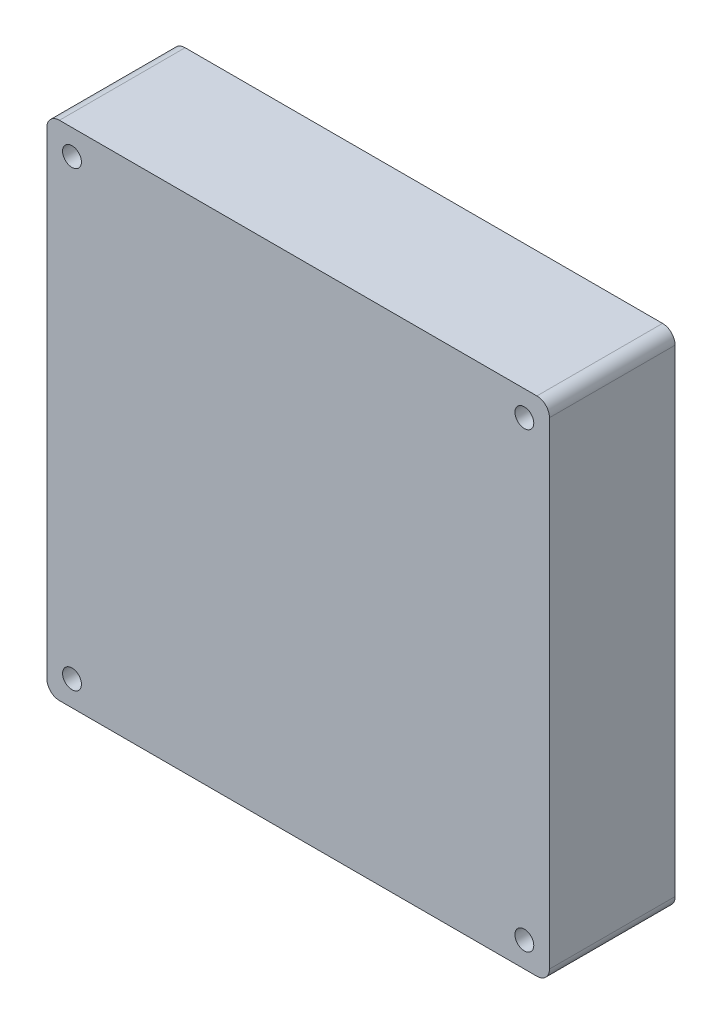
SolidWorks part; units mm, degrees
ref_plane "Front Plane" through (0, 0, 0) normal (0, 0, 1) x (1, 0, 0)
ref_plane "Top Plane" through (0, 0, 0) normal (0, 1, 0) x (1, 0, 0)
ref_plane "Right Plane" through (0, 0, 0) normal (1, 0, 0) x (0, 0, -1)
sketch "Sketch1" plane through (0, 0, 0) normal (0, 0, 1) x (1, 0, 0)
  line L1 (0, 0) -> (-40, 0)
  line L2 (0, 0) -> (0, 40)
  line L3 (0, 40) -> (-40, 40)
  line L4 (-40, 0) -> (-40, 40)
  dimension "D1" = 40
extrude "Boss-Extrude1" add sketch "Sketch1" along normal blind 10
sketch "Sketch2" plane through (0, 0, 10) normal (0, 0, 1) x (1, 0, 0)
  line L0 (-40, 0) -> (0, 40) construction
  line L1 (0, 0) -> (-40, 40) construction
  line L10 (-2, 2) -> (-2, 38)
  line L11 (-38, 2) -> (-2, 2)
  line L12 (-38, 38) -> (-38, 2)
  line L13 (-2, 38) -> (-38, 38)
  line L14 (-2, 2) -> (-2, 38) construction
  line L15 (-38, 2) -> (-2, 2) construction
  line L16 (-38, 38) -> (-38, 2) construction
  line L17 (-2, 38) -> (-38, 38) construction
  circle A0 centre (-38, 38) radius 0.75
  circle A1 centre (-2, 38) radius 0.75
  circle A2 centre (-2, 2) radius 0.75
  circle A3 centre (-38, 2) radius 0.75
  dimension "D1" = 2
  dimension "D2" = 1.5
extrude "Cut-Extrude1" cut sketch "Sketch2" against normal blind 10
fillet "Fillet1" radius 1 4 edges at (0, 0, 5) (-40, 0, 5) (-40, 40, 5) (0, 40, 5)
